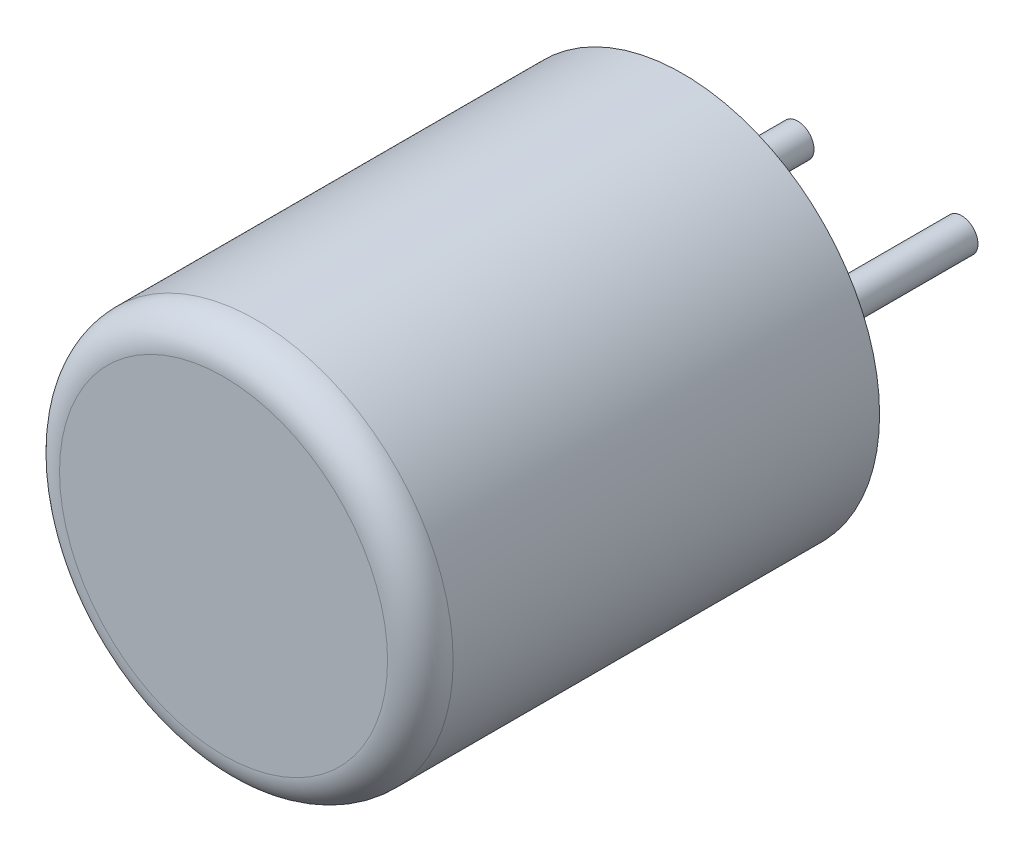
SolidWorks part; units mm, degrees
ref_plane "Спереди" through (0, 0, 0) normal (0, 0, 1) x (1, 0, 0)
ref_plane "Сверху" through (0, 0, 0) normal (0, 1, 0) x (1, 0, 0)
ref_plane "Справа" through (0, 0, 0) normal (1, 0, 0) x (0, 0, -1)
sketch "Эскиз1" plane through (0, 0, 0) normal (0, 0, 1) x (1, 0, 0)
  circle A0 centre (0, 0) radius 3
  dimension "D1" = 6
extrude "Вытянуть1" add sketch "Эскиз1" along normal blind 7
sketch "Эскиз2" plane through (0, 0, 0) normal (0, 0, -1) x (-1, 0, 0)
  line L0 (-8.813, 0) -> (9.6479, 0) construction
  line L1 (0, 0) -> (0, 4.6268) construction
  circle A0 centre (-1.25, 0) radius 0.25
  circle A1 centre (1.25, 0) radius 0.25
  dimension "D1" = 2.5
  dimension "D2" = 0.5
extrude "Вытянуть2" add sketch "Эскиз2" along normal blind 3
fillet "Скругление1" radius 0.5 1 edges at (3, 0, 7)
